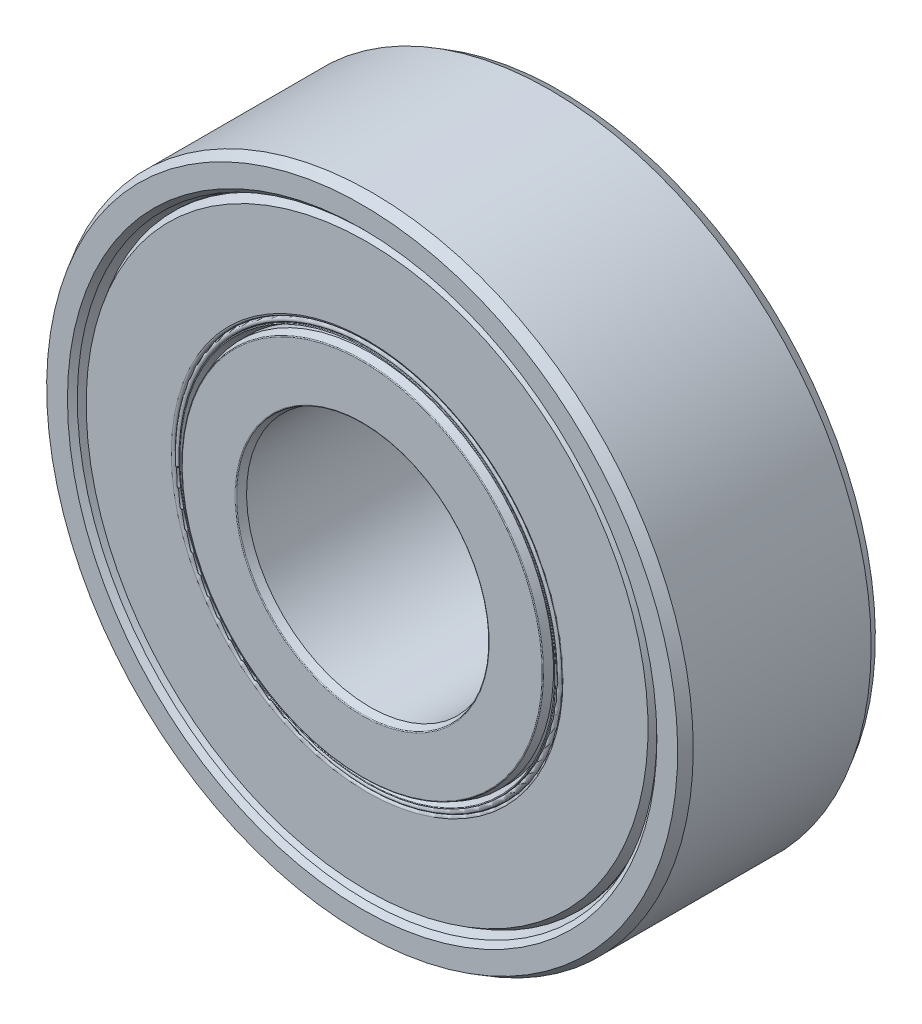
SolidWorks part; units mm, degrees
ref_plane "Front Plane" through (0, 0, 0) normal (0, 0, 1) x (1, 0, 0)
ref_plane "Top Plane" through (0, 0, 0) normal (0, 1, 0) x (1, 0, 0)
ref_plane "Right Plane" through (0, 0, 0) normal (1, 0, 0) x (0, 0, -1)
sketch "Sketch1" plane through (0, 0, 0) normal (0, 0, 1) x (1, 0, 0)
  line L0 (-13, 0) -> (13, 0) construction
  line L1 (-5, 0) -> (5, 0) construction
  circle A0 centre (0, 0) radius 5 construction
  circle A1 centre (0, 0) radius 13 construction
  point P3 (0, 0)
  point P6 (0, 0)
  point P7 (0, -5)
  point P11 (0, -13)
  point P12 (0, 5)
  point P13 (0, 13)
  dimension "OD" = 26
  dimension "ID" = 10
sketch "Sketch2" plane through (0, 0, 0) normal (1, 0, 0) x (0, 0, -1)
  line L0 (-4, 13) -> (4, 13) construction
  line L1 (0, 13) -> (0, -13) construction
  line L2 (3.6, 13) -> (-3.6, 13)
  line L3 (-3.6, 13) -> (-4, 12.7691)
  line L4 (-4, 12.7691) -> (-4, 11.928)
  line L5 (-3.366, 11.57) -> (-1.864, 11.57)
  line L6 (3.366, 11.57) -> (1.864, 11.57)
  line L7 (4, 12.7691) -> (4, 11.928)
  line L8 (3.6, 13) -> (4, 12.7691)
  line L9 (-1.864, 11.57) -> (-1.864, 13) construction
  line L10 (-1.864, 12.285) -> (0, 12.285) construction
  line L11 (0, 13) -> (0, -13) construction
  line L12 (-4, 0) -> (4, 0) construction
  line L13 (4, 5) -> (-4, 5) construction
  line L14 (-4, 5) -> (-4, -5) construction
  line L15 (-4, -5) -> (4, -5) construction
  line L16 (4, 13) -> (4, -13) construction
  line L20 (-3.366, 11.57) -> (-3.8, 11.728)
  line L21 (-3.8, 11.728) -> (-4, 11.928)
  line L26 (3.8, 11.728) -> (4, 11.928)
  line L27 (3.366, 11.57) -> (3.8, 11.728)
  arc A0 (-1.864, 11.57) -> (1.864, 11.57) centre (0, 9.4978) cw
  circle A1 centre (0, 9.4978) radius 2.7872 construction
  point P17 (0, 0)
  point P21 (0, 13)
  point P30 (0, -5)
  dimension "Width" = 8
  dimension "D3" = 3.728
  dimension "For Shaft Diameter" = 10
  dimension "For Housing ID" = 26
  dimension "D4" = 23.14
  dimension "D2" = 20
  dimension "D5" = 45
  dimension "D1" = 30
  dimension "D6" = 0.4
  dimension "D7" = 0.2
sketch "Sketch3" plane through (0, 0, 0) normal (1, 0, 0) x (0, 0, -1)
  line L14 (-3.366, 11.57) -> (-3.8, 11.728) construction
  line L15 (-3.8, 11.728) -> (-4, 11.928) construction
  line L16 (-4, 12.7691) -> (-4, 11.928) construction
  line L17 (-3.6, 13) -> (-4, 12.7691) construction
  line L18 (3.6, 13) -> (-3.6, 13) construction
  line L19 (3.6, 13) -> (4, 12.7691) construction
  line L20 (4, 12.7691) -> (4, 11.928) construction
  line L21 (3.8, 11.728) -> (4, 11.928) construction
  line L22 (3.366, 11.57) -> (3.8, 11.728) construction
  line L23 (3.366, 11.57) -> (1.864, 11.57) construction
  line L24 (-3.366, 11.57) -> (-1.864, 11.57) construction
  line L25 (-3.366, 11.57) -> (-3.8, 11.728)
  line L26 (-3.8, 11.728) -> (-4, 11.928)
  line L27 (-4, 12.7691) -> (-4, 11.928)
  line L28 (-3.6, 13) -> (-4, 12.7691)
  line L29 (3.6, 13) -> (-3.6, 13)
  line L30 (3.6, 13) -> (4, 12.7691)
  line L31 (4, 12.7691) -> (4, 11.928)
  line L32 (3.8, 11.728) -> (4, 11.928)
  line L33 (3.366, 11.57) -> (3.8, 11.728)
  line L34 (3.366, 11.57) -> (1.864, 11.57)
  line L35 (-3.366, 11.57) -> (-1.864, 11.57)
  arc A2 (1.864, 11.57) -> (-1.864, 11.57) centre (0, 9.4978) ccw construction
  arc A3 (1.864, 11.57) -> (-1.864, 11.57) centre (0, 9.4978) ccw
revolve "Revolve1" add sketch "Sketch3" angle 360 about L12
sketch "Sketch4" plane through (0, 0, 0) normal (1, 0, 0) x (0, 0, -1)
  line L0 (0, 13) -> (0, -13) construction
  line L1 (0, 13) -> (0, -13) construction
  line L2 (-3.68, 5) -> (-3.9737, 5.1069)
  line L3 (-4, 5.1445) -> (-4, 7.2811)
  line L4 (3.68, 7.4256) -> (3.9737, 7.3187)
  line L5 (-3.68, 7.4256) -> (-1.864, 7.4256)
  line L6 (-3.68, 5) -> (3.68, 5)
  line L7 (4, 12.7691) -> (4, 11.928) construction
  line L8 (3.68, 5) -> (3.9737, 5.1069)
  line L9 (1.864, 7.4256) -> (1.864, 5) construction
  line L10 (4, 5.1445) -> (4, 7.2811)
  line L11 (3.68, 7.4256) -> (1.864, 7.4256)
  line L12 (-3.68, 7.4256) -> (-3.9737, 7.3187)
  line L14 (1.864, 6.2128) -> (4, 6.2128) construction
  circle A0 centre (0, 9.4978) radius 2.7872 construction
  arc A1 (1.864, 7.4256) -> (-1.864, 7.4256) centre (0, 9.4978) cw
  arc A2 (3.9737, 7.3187) -> (4, 7.2811) centre (3.96, 7.2811) cw
  arc A3 (-3.9737, 7.3187) -> (-4, 7.2811) centre (-3.96, 7.2811) ccw
  arc A4 (3.9737, 5.1069) -> (4, 5.1445) centre (3.96, 5.1445) ccw
  arc A5 (-3.9737, 5.1069) -> (-4, 5.1445) centre (-3.96, 5.1445) cw
  point P14 (4, 5.1165)
  dimension "D2" = 0.04
  dimension "D1" = 20
  dimension "D3" = 0.32
revolve "Revolve2" add sketch "Sketch4" angle 360 about L12
sketch "Sketch5" plane through (0, 0, 0) normal (1, 0, 0) x (0, 0, -1)
  line L0 (-2.7872, 9.4978) -> (2.7872, 9.4978)
  arc A2 (-2.7872, 9.4978) -> (2.7872, 9.4978) centre (0, 9.4978) cw
  arc A3 (1.864, 11.57) -> (-1.864, 11.57) centre (0, 9.4978) ccw construction
revolve "Revolve3" add sketch "Sketch5" angle 360 about L0
pattern_circular "CirPattern1" count 10 over 360 about axis through (0, 0, 0) along (0, 0, 1) of bodies 104
sketch "Sketch6" plane through (0, 0, 0) normal (1, 0, 0) x (0, 0, -1)
  line L1 (-3.4536, 11.57) -> (-2.7872, 11.57)
  line L2 (-3.8, 11.37) -> (-3.8, 7.9256)
  line L3 (-3.7, 7.8256) -> (-2.7872, 7.8256)
  line L4 (-2.7872, 11.57) -> (-2.7872, 7.8256)
  line L6 (-3.6, 13) -> (-4, 12.7691) construction
  line L7 (0, 13) -> (0, 5) construction
  line L8 (3.7, 7.8256) -> (2.7872, 7.8256)
  line L9 (2.7872, 11.57) -> (2.7872, 7.8256)
  line L10 (3.4536, 11.57) -> (2.7872, 11.57)
  line L11 (3.8, 11.37) -> (3.8, 7.9256)
  line L13 (-3.68, 7.4256) -> (-1.864, 7.4256) construction
  line L14 (-3.8, 11.37) -> (-3.4536, 11.57)
  line L15 (-3.366, 11.57) -> (-1.864, 11.57) construction
  line L16 (3.8, 11.37) -> (3.4536, 11.57)
  arc A0 (-3.8, 7.9256) -> (-3.7, 7.8256) centre (-3.7, 7.9256) ccw
  circle A1 centre (0, 9.4978) radius 2.7872 construction
  arc A2 (3.8, 7.9256) -> (3.7, 7.8256) centre (3.7, 7.9256) cw
  point P10 (-3.8, 12.8845)
  point P26 (-3.8, 7.8256)
  dimension "D3" = 0.1
  dimension "D1" = 0.4
  dimension "D2" = 0.2
revolve "Revolve4" add sketch "Sketch6" angle 360 about L12
sketch "Sketch7" plane through (0, 0, 0) normal (1, 0, 0) x (0, 0, -1)
  line L0 (-2.7872, 7.4256) -> (-3.3439, 7.4256)
  line L5 (-3.3439, 7.4256) -> (-3.7868, 7.5868)
  line L6 (-3.78, 7.6256) -> (-3.7, 7.6256)
  line L7 (0, 6.7106) -> (0, 5) construction
  line L8 (0, 13) -> (0, -13) construction
  line L9 (-3.7, 7.8256) -> (-2.7872, 7.8256)
  line L12 (-2.7872, 7.8256) -> (-2.7872, 7.4256)
  line L13 (-3.68, 7.4256) -> (-1.864, 7.4256) construction
  line L14 (-3.7, 7.8256) -> (-2.7872, 7.8256) construction
  line L15 (-2.7872, 11.57) -> (-2.7872, 7.8256) construction
  line L16 (2.7872, 7.8256) -> (2.7872, 7.4256)
  line L17 (3.7, 7.8256) -> (2.7872, 7.8256)
  line L18 (3.78, 7.6256) -> (3.7, 7.6256)
  line L19 (3.3439, 7.4256) -> (3.7868, 7.5868)
  line L20 (2.7872, 7.4256) -> (3.3439, 7.4256)
  circle A2 centre (0, 9.4978) radius 2.7872 construction
  arc A5 (-3.7868, 7.5868) -> (-3.78, 7.6256) centre (-3.78, 7.6056) cw
  arc A6 (-3.7, 7.6256) -> (-3.7, 7.8256) centre (-3.7, 7.7256) cw
  arc A7 (3.7, 7.6256) -> (3.7, 7.8256) centre (3.7, 7.7256) ccw
  arc A8 (3.7868, 7.5868) -> (3.78, 7.6256) centre (3.78, 7.6056) ccw
  point P14 (-3.8, 7.7256)
  point P27 (-2.7872, 7.6256)
  point P36 (-3.8, 7.6056)
  dimension "D1" = 20
  dimension "D2" = 0.02
revolve "Revolve5" add sketch "Sketch7" angle 360 about L12
equation "\"D3@Sketch2\"=\"Width@Sketch2\" *.466"
equation "\"D4@Sketch2\"=\"OD@Sketch1\"*.89"
equation "\"D1@Sketch6\"=(\"OD@Sketch1\"-\"ID@Sketch1\")*.025"
equation "\"D2@Sketch6\"=\"D1@Sketch6\"*.5"
equation "\"D3@Sketch6\"=\"D1@Sketch6\"*.25"
equation "\"D3@Sketch4\"=\"Width@Sketch2\"*.04"
equation "\"D2@Sketch4\"=\"D3@Sketch4\"*.125"
equation "\"D6@Sketch2\"=\"Width@Sketch2\"*.05"
equation "\"D7@Sketch2\"=\"D6@Sketch2\"*.5"
equation "\"D2@Sketch7\"=\"D6@Sketch2\"*.05"
